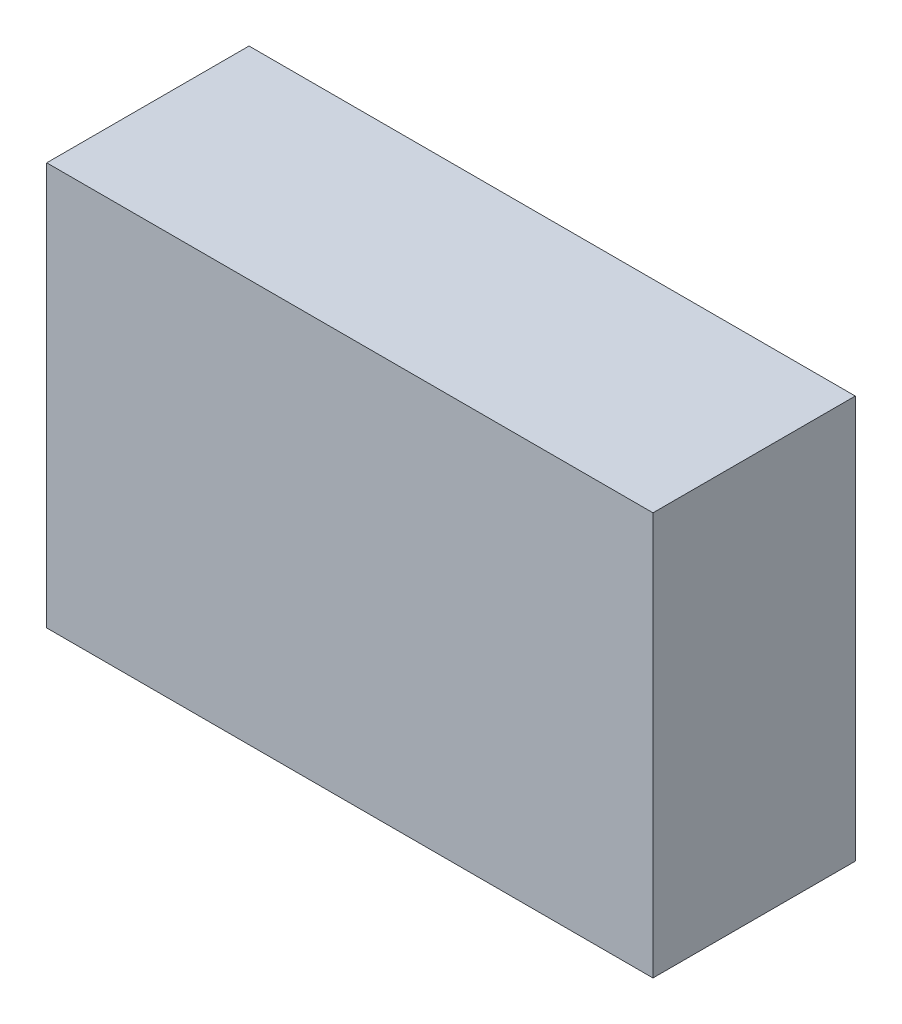
SolidWorks part; units mm, degrees
ref_plane "Front Plane" through (0, 0, 0) normal (0, 0, 1) x (1, 0, 0)
ref_plane "Top Plane" through (0, 0, 0) normal (0, 1, 0) x (1, 0, 0)
ref_plane "Right Plane" through (0, 0, 0) normal (1, 0, 0) x (0, 0, -1)
sketch "Sketch1" plane through (0, 0, 0) normal (0, 0, 1) x (1, 0, 0)
  line L0 (-1.4984, 1.0084) -> (1.4984, 1.0084)
  line L1 (1.4984, 1.0084) -> (1.4984, -0.983)
  line L2 (1.4984, -0.983) -> (-1.4984, -0.983)
  line L3 (-1.4984, -0.983) -> (-1.4984, 1.0084)
extrude "Component_Outline" add sketch "Sketch1" along normal blind 1 separate body
sketch3d "3DSketch1"
  line L0 (0, 0, 0) -> (1, 0, 0)
  line L1 (0, 0, 0) -> (0, 1, 0)
  line L2 (0, 0, 0) -> (0, 0, 1)
  point P0 (0, 0, 0)
